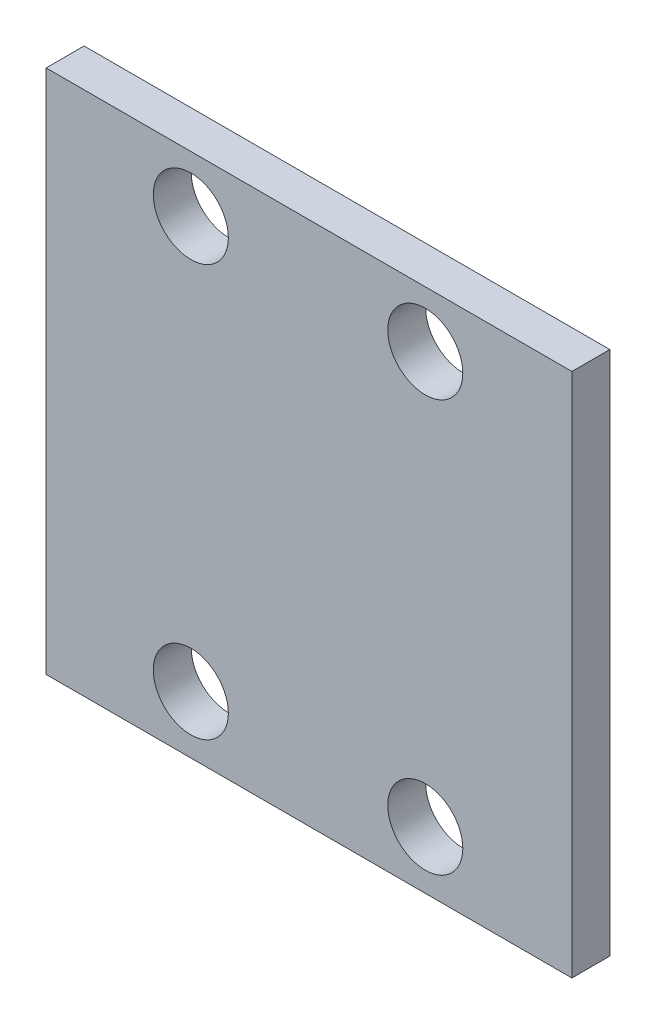
SolidWorks part; units mm, degrees
ref_plane "Front Plane" through (0, 0, 0) normal (0, 0, 1) x (1, 0, 0)
ref_plane "Top Plane" through (0, 0, 0) normal (0, 1, 0) x (1, 0, 0)
ref_plane "Right Plane" through (0, 0, 0) normal (1, 0, 0) x (0, 0, -1)
other "Mesh1"
other "Imported Mesh-1"
other "Imported Mesh-2"
other "Imported Mesh-3"
other "Imported Mesh-4"
other "Imported Mesh-5"
other "Imported Mesh-6"
other "Imported Mesh-7"
other "Imported Mesh-8"
other "Imported Mesh-9"
other "Imported Mesh-10"
other "Imported Mesh-11"
other "Imported Mesh-12"
other "Imported Mesh-13"
sketch "Sketch1" plane through (0, 0, 0) normal (0, 0, 1) x (1, 0, 0)
  line L1 (0, 0) -> (22.8589, 0)
  line L2 (0, 0) -> (0, 22.8398)
  line L3 (0, 22.8398) -> (22.8589, 22.8398)
  line L4 (22.8589, 0) -> (22.8589, 22.8398)
  line L5 (0, 0) -> (22.8589, 22.8398) construction
  line L6 (0, 22.8398) -> (22.8589, 0) construction
  point P0 (11.4294, 11.4199)
extrude "Boss-Extrude1" add sketch "Sketch1" along normal mid plane 1.65
hole_wizard "#4 Clearance Hole1" positions "Sketch2" profile "Sketch3" hole size "#4" standard "ANSI Inch" end condition through all
sketch "Sketch2" plane through (0, 0, 0.825) normal (0, 0, 1) x (1, 0, 0)
  point P0 (16.4835, 20.4008)
  point P2 (6.2897, 20.4008)
  point P4 (6.2897, 2.5033)
  point P6 (16.4835, 2.5033)
sketch "Sketch3" plane through (16.4835, 20.4008, 0.825) normal (1, 0, 0) x (0, -1, 0)
  line L0 (0, 0) -> (0, 1.65)
  line L1 (0, 1.65) -> (1.6319, 1.65)
  line L2 (1.6319, 1.65) -> (1.6319, 0)
  line L5 (1.6319, 0) -> (0, 0)
  line L11 (0, -6.35) -> (0, 107.95) construction
  dimension "Thru Hole Dia." = 3.2639
  dimension "Thru Hole Depth" = 1.65
